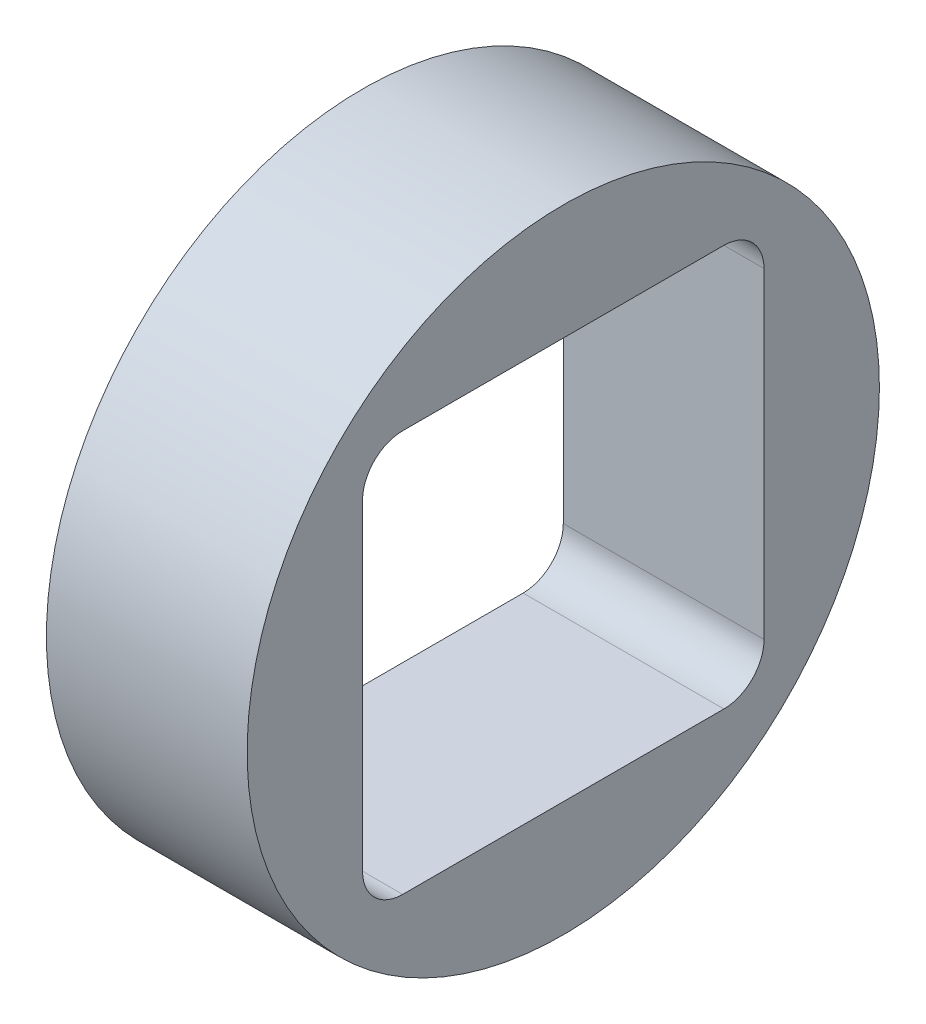
SolidWorks part; units mm, degrees
ref_plane "Front" through (0, 0, 0) normal (0, 0, 1) x (1, 0, 0)
ref_plane "Top" through (0, 0, 0) normal (0, 1, 0) x (1, 0, 0)
ref_plane "Right" through (0, 0, 0) normal (1, 0, 0) x (0, 0, -1)
sketch "Sketch1" plane through (0, 0, 0) normal (1, 0, 0) x (0, 0, -1)
  line L1 (3.175, -3.175) -> (-3.175, -3.175)
  line L2 (3.175, -3.175) -> (3.175, 3.175)
  line L3 (3.175, 3.175) -> (-3.175, 3.175)
  line L4 (-3.175, -3.175) -> (-3.175, 3.175)
  line L5 (3.175, -3.175) -> (-3.175, 3.175) construction
  line L6 (3.175, 3.175) -> (-3.175, -3.175) construction
  circle A0 centre (0, 0) radius 5
  point P0 (0, 0)
  dimension "D1" = 10
  dimension "D2" = 6.35
extrude "Boss-Extrude1" add sketch "Sketch1" along normal blind 3.175 contours A0 | L4 L3 L2 L1
fillet "Fillet1" radius 0.635 4 edges at (1.5875, -3.175, -3.175) (1.5875, -3.175, 3.175) (1.5875, 3.175, 3.175) (1.5875, 3.175, -3.175)
